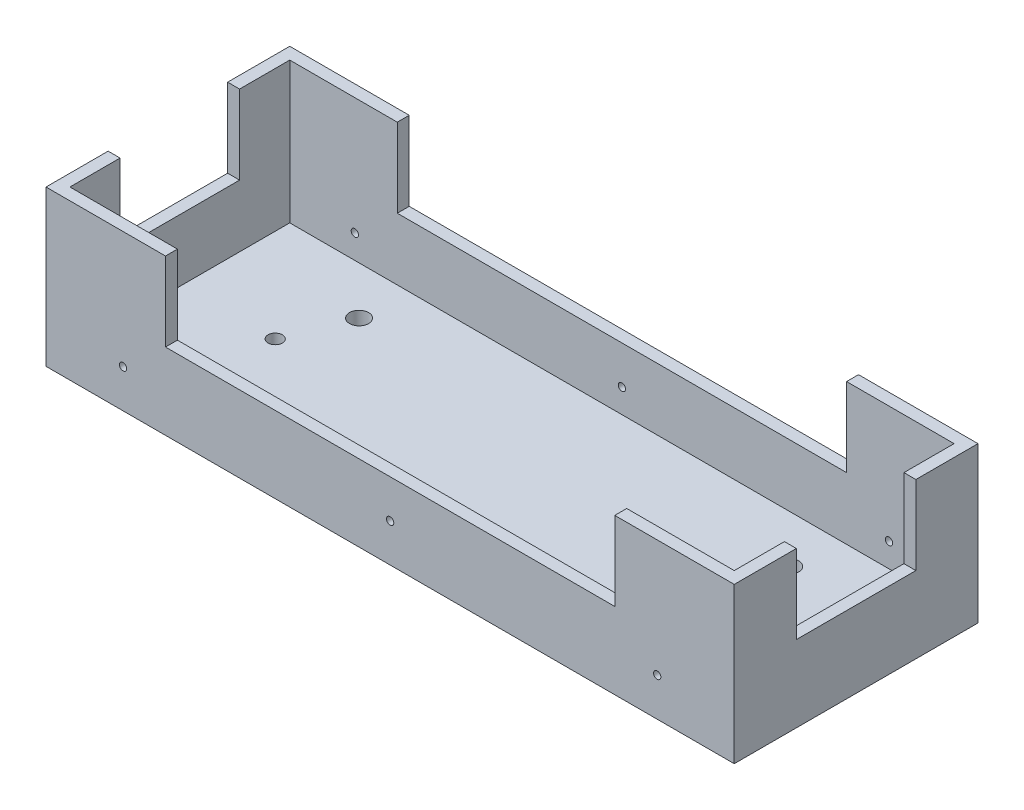
SolidWorks part; units mm, degrees
ref_plane "Front Plane" through (0, 0, 0) normal (0, 0, 1) x (1, 0, 0)
ref_plane "Top Plane" through (0, 0, 0) normal (0, 1, 0) x (1, 0, 0)
ref_plane "Right Plane" through (0, 0, 0) normal (1, 0, 0) x (0, 0, -1)
sketch "Sketch1" plane through (0, 0, 0) normal (0, 1, 0) x (1, 0, 0)
  line L1 (72, 25.5) -> (-72, 25.5)
  line L2 (72, 25.5) -> (72, -25.5)
  line L3 (72, -25.5) -> (-72, -25.5)
  line L4 (-72, 25.5) -> (-72, -25.5)
  line L5 (72, 25.5) -> (-72, -25.5) construction
  line L6 (72, -25.5) -> (-72, 25.5) construction
  point P0 (0, 0)
  dimension "D1" = 144
  dimension "D2" = 51
extrude "Boss-Extrude1" add sketch "Sketch1" along normal blind 3
sketch "Sketch2" plane through (0, 3, 0) normal (0, 1, 0) x (1, 0, 0)
  line L1 (72, 25.5) -> (-72, 25.5)
  line L2 (72, 25.5) -> (72, -25.5)
  line L3 (72, -25.5) -> (-72, -25.5)
  line L4 (-72, 25.5) -> (-72, -25.5)
  line L5 (72, 25.5) -> (-72, -25.5) construction
  line L6 (72, -25.5) -> (-72, 25.5) construction
  line L7 (69.5, -23) -> (-69.5, -23)
  line L8 (69.5, -23) -> (69.5, 23)
  line L9 (69.5, 23) -> (-69.5, 23)
  line L10 (-69.5, -23) -> (-69.5, 23)
  line L11 (69.5, -23) -> (-69.5, 23) construction
  line L12 (69.5, 23) -> (-69.5, -23) construction
  point P0 (0, 0)
  point P7 (0, 0)
  dimension "D1" = 2.5
  dimension "D2" = 2.5
extrude "Boss-Extrude2" add sketch "Sketch2" along normal blind 16 from surface at -3 starting at face at (0, 0, 0)
sketch "Sketch3" plane through (0, 16, 0) normal (0, 1, 0) x (1, 0, 0)
  line L0 (0, 25.5) -> (0, -25.5) construction
  line L1 (-72, 25.5) -> (72, 25.5) construction
  line L2 (72, -25.5) -> (-72, -25.5) construction
  line L3 (-72, 0) -> (72, 0) construction
  line L4 (-72, -25.5) -> (-72, 25.5) construction
  line L5 (72, 25.5) -> (72, -25.5) construction
  line L6 (-72, 25.5) -> (-72, 12.5)
  line L7 (-72, 12.5) -> (-69.5, 12.5)
  line L8 (-69.5, -23) -> (-69.5, 23) construction
  line L9 (-69.5, 12.5) -> (-69.5, 23)
  line L10 (-69.5, 23) -> (-47, 23)
  line L11 (-69.5, 23) -> (69.5, 23) construction
  line L12 (-47, 23) -> (-47, 25.5)
  line L13 (-47, 25.5) -> (-72, 25.5)
  line L14 (47, 25.5) -> (72, 25.5)
  line L15 (47, 23) -> (47, 25.5)
  line L16 (69.5, 23) -> (47, 23)
  line L17 (69.5, 12.5) -> (69.5, 23)
  line L18 (72, 12.5) -> (69.5, 12.5)
  line L19 (72, 25.5) -> (72, 12.5)
  line L20 (72, -25.5) -> (72, -12.5)
  line L21 (72, -12.5) -> (69.5, -12.5)
  line L22 (69.5, -12.5) -> (69.5, -23)
  line L23 (69.5, -23) -> (47, -23)
  line L24 (47, -23) -> (47, -25.5)
  line L25 (47, -25.5) -> (72, -25.5)
  line L26 (-47, -25.5) -> (-72, -25.5)
  line L27 (-47, -23) -> (-47, -25.5)
  line L28 (-69.5, -23) -> (-47, -23)
  line L29 (-69.5, -12.5) -> (-69.5, -23)
  line L30 (-72, -12.5) -> (-69.5, -12.5)
  line L31 (-72, -25.5) -> (-72, -12.5)
  dimension "D1" = 13
  dimension "D2" = 25
extrude "Boss-Extrude3" add sketch "Sketch3" along normal blind 16.5
sketch "Sketch4" plane through (0, 0, 0) normal (0, -1, 0) x (1, 0, 0)
  line L0 (-72, 0) -> (72, 0) construction
  line L1 (-72, -25.5) -> (-72, 25.5) construction
  line L2 (72, 25.5) -> (72, -25.5) construction
  line L3 (-45, 25.5) -> (-45, -25.5) construction
  line L4 (-72, 25.5) -> (72, 25.5) construction
  line L5 (72, -25.5) -> (-72, -25.5) construction
  line L6 (-47, -25.5) -> (-72, -25.5) construction
  line L7 (0, 25.5) -> (0, -25.5) construction
  line L8 (45, 25.5) -> (45, -25.5) construction
  circle A0 centre (-45, -13) radius 2
  circle A1 centre (-45, 13) radius 2
  circle A2 centre (45, 13) radius 2
  circle A3 centre (45, -13) radius 2
  circle A4 centre (-50, -0.45) radius 1.5
  circle A5 centre (50, -0.45) radius 1.5
  point P16 (-59.5, -25.5)
  point P19 (-47, 13)
  point P28 (47, 13)
  dimension "D3" = 4
  dimension "D7" = 3
  dimension "D1" = 12.5
  dimension "D2" = 12.5
  dimension "D4" = 25
  dimension "D5" = 22
  dimension "D6" = 25.05
extrude "Cut-Extrude1" cut sketch "Sketch4" against normal through all
sketch "Sketch5" plane through (0, 0, 25.5) normal (0, 0, 1) x (1, 0, 0)
  line L0 (-55.88, 8) -> (0, 8) construction
  line L1 (0, 8) -> (55.88, 8) construction
  line L2 (0, 8) -> (0, 0) construction
  line L3 (0, 8) -> (0, 16) construction
  line L4 (47, 16) -> (-47, 16) construction
  circle A0 centre (-55.88, 8) radius 0.762
  circle A1 centre (55.88, 8) radius 0.762
  circle A2 centre (0, 8) radius 0.762
  dimension "D1" = 1.524
  dimension "D2" = 55.88
extrude "Cut-Extrude2" cut sketch "Sketch5" against normal through all
equation "\"D2@Sketch4\"=\"D1@Sketch4\""
